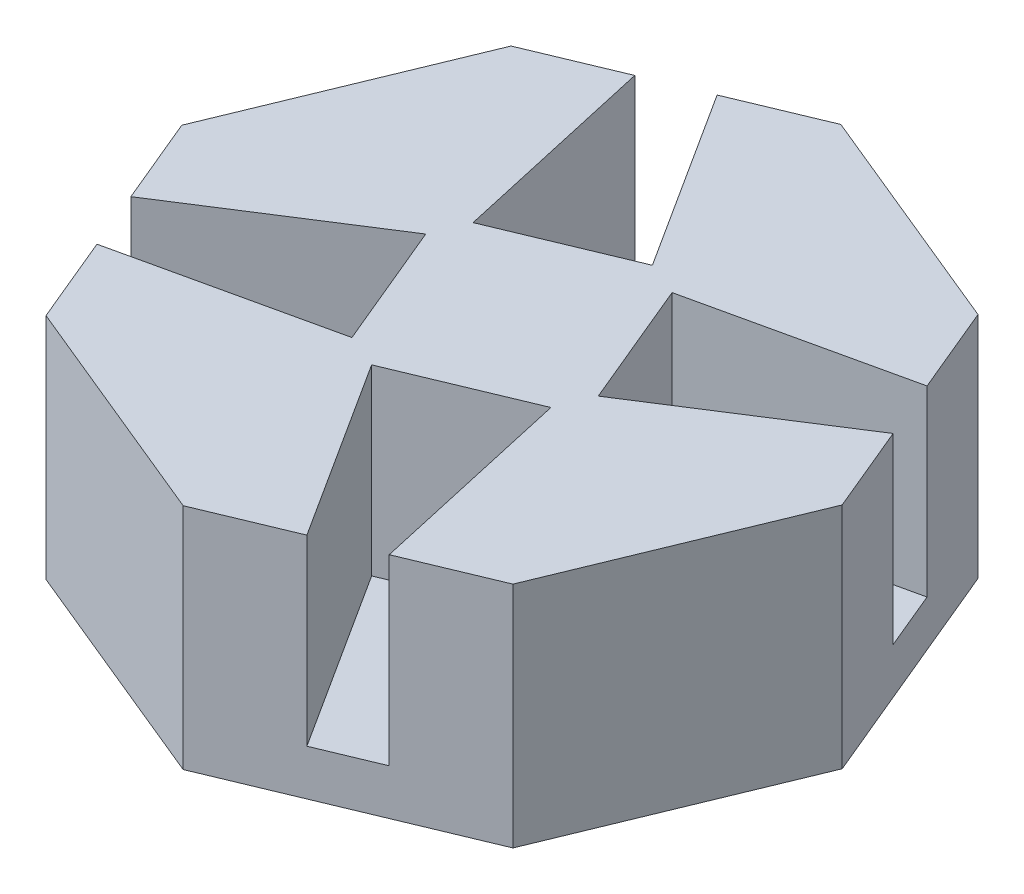
SolidWorks part; units mm, degrees
ref_plane "Front Plane" through (0, 0, 0) normal (0, 0, 1) x (1, 0, 0)
ref_plane "Top Plane" through (0, 0, 0) normal (0, 1, 0) x (1, 0, 0)
ref_plane "Right Plane" through (0, 0, 0) normal (1, 0, 0) x (0, 0, -1)
sketch "Sketch1" plane through (0, 0, 0) normal (0, 1, 0) x (1, 0, 0)
  line L1 (-0.112, 54.9379) -> (-38.9262, 38.7678)
  line L2 (-38.9262, 38.7678) -> (-54.9379, -0.112)
  line L3 (-54.9379, -0.112) -> (-38.7678, -38.9262)
  line L4 (-38.7678, -38.9262) -> (0.112, -54.9379)
  line L5 (0.112, -54.9379) -> (38.9262, -38.7678)
  line L6 (38.9262, -38.7678) -> (54.9379, 0.112)
  line L7 (54.9379, 0.112) -> (38.7678, 38.9262)
  line L8 (38.7678, 38.9262) -> (-0.112, 54.9379)
  circle A0 centre (0, 0) radius 50.7561 construction
  dimension "D2" = 101.5123
  dimension "D1" = 38.8798
  dimension "D3" = 42.0478
extrude "Boss-Extrude1" add sketch "Sketch1" along normal blind 38.1
sketch "Sketch2" plane through (0, 38.1, 0) normal (0, 1, 0) x (1, 0, 0)
  line L0 (19.5191, -46.8529) -> (6.0393, -14.4964) construction
  line L1 (-4.5117, -18.892) -> (14.6734, -48.8716)
  line L2 (0.112, -54.9379) -> (38.9262, -38.7678) construction
  line L3 (16.5903, -10.1009) -> (24.3648, -44.8341)
  line L4 (-4.5117, -18.892) -> (16.5903, -10.1009)
  line L5 (-18.892, 4.5117) -> (-48.8716, -14.6734)
  line L6 (-18.892, 4.5117) -> (-10.1009, -16.5903)
  line L7 (-10.1009, -16.5903) -> (-44.8341, -24.3648)
  line L8 (-46.8529, -19.5191) -> (-14.4964, -6.0393) construction
  line L9 (4.5117, 18.892) -> (-14.6734, 48.8716)
  line L10 (4.5117, 18.892) -> (-16.5903, 10.1009)
  line L11 (-16.5903, 10.1009) -> (-24.3648, 44.8341)
  line L12 (-19.5191, 46.8529) -> (-6.0393, 14.4964) construction
  line L13 (18.892, -4.5117) -> (48.8716, 14.6734)
  line L14 (18.892, -4.5117) -> (10.1009, 16.5903)
  line L15 (10.1009, 16.5903) -> (44.8341, 24.3648)
  line L16 (46.8529, 19.5191) -> (14.4964, 6.0393) construction
  point P30 (0, 0)
  line M17 (-0.112, 54.9379) -> (-38.9262, 38.7678)
  line M19 (-54.9379, -0.112) -> (-38.7678, -38.9262)
  line M21 (0.112, -54.9379) -> (38.9262, -38.7678)
  line M23 (54.9379, 0.112) -> (38.7678, 38.9262)
  dimension "D1" = 15.7041
  dimension "D2" = 22.86
  dimension "D3" = 35.052
  dimension "D4" = 80
  dimension "D5" = 80
  dimension "D6" = 4
  dimension "D7" = 14.4964
  dimension "D8" = 5.5891
extrude "Cut-Extrude1" cut sketch "Sketch2" along direction (0, 1, 0) on the side against the normal blind 30.48 contours L4 L1 L3 M21 | L7 L6 L5 M19 | L11 L10 L9 M17 | L15 L14 L13 M23
